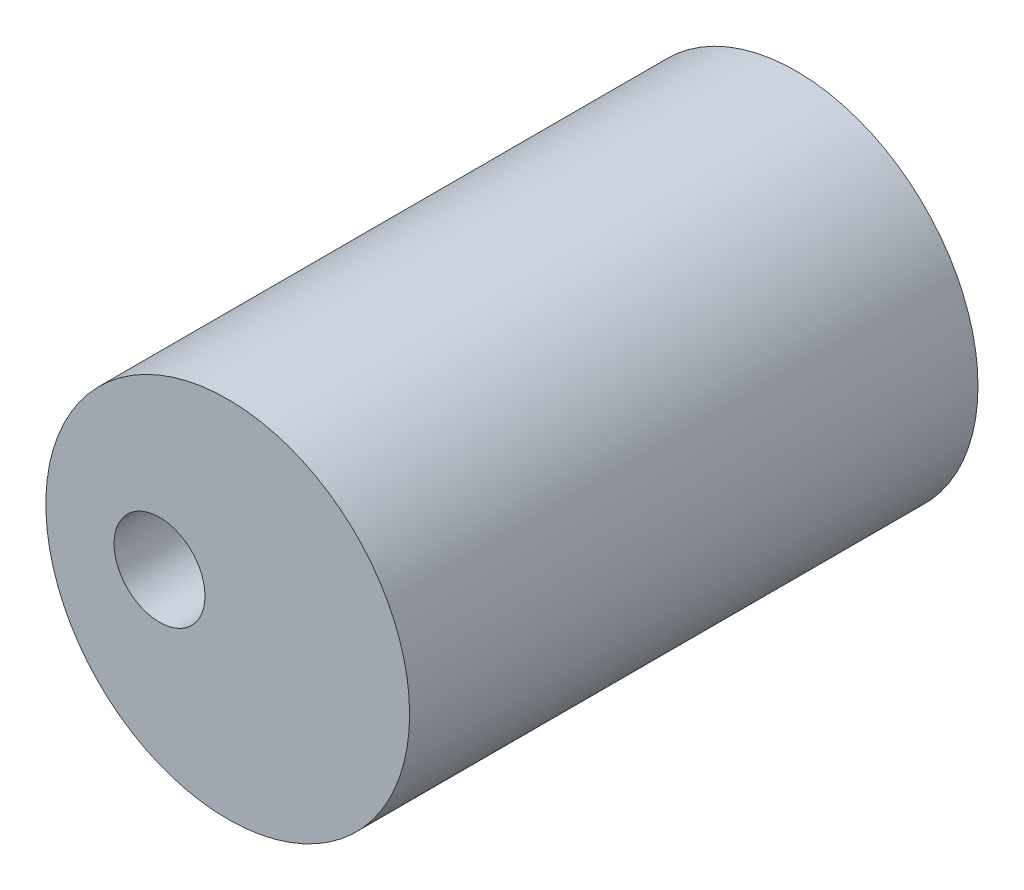
SolidWorks part; units mm, degrees
ref_plane "Front Plane" through (0, 0, 0) normal (0, 0, 1) x (1, 0, 0)
ref_plane "Top Plane" through (0, 0, 0) normal (0, 1, 0) x (1, 0, 0)
ref_plane "Right Plane" through (0, 0, 0) normal (1, 0, 0) x (0, 0, -1)
sketch "Sketch1" plane through (0, 0, 0) normal (0, 0, 1) x (1, 0, 0)
  circle A0 centre (0, 0) radius 40
  dimension "D1" = 80
extrude "Boss-Extrude1" add sketch "Sketch1" along normal blind 125
ref_plane "Plane1" through (0, 0, 18.19) normal (0, 0, 1) x (1, 0, 0)
sketch "Sketch9" plane through (0, 0, 18.19) normal (0, 0, 1) x (1, 0, 0)
  circle A0 centre (0, 0) radius 16
  dimension "D1" = 32
extrude "Cut-Extrude3" cut sketch "Sketch9" along normal blind 38.79
sketch "Sketch11" plane through (0, 0, 56.98) normal (0, 0, -1) x (-1, 0, 0)
  circle A0 centre (0, 0) radius 2.5
  dimension "D1" = 5
extrude "Cut-Extrude5" cut sketch "Sketch11" against normal blind 10
sketch "Sketch10" plane through (0, 0, 0) normal (0, 0, 1) x (1, 0, 0)
  circle A0 centre (0, 0) radius 5
  dimension "D1" = 10
extrude "Cut-Extrude4" cut sketch "Sketch10" along normal blind 38.5
sketch "Sketch12" plane through (0, 0, 0) normal (1, 0, 0) x (0, 0, -1)
  circle A0 centre (-64, 0) radius 2.5
  point P2 (0, 0)
  point P3 (-96.45, -2.5)
  point P4 (-93.962, 0)
  point P5 (-92.8736, 0)
  point P6 (-93.2559, -2.5)
  point P7 (-74.8159, 0)
  dimension "D1" = 5
  dimension "D2" = 64
extrude "Cut-Extrude7" cut sketch "Sketch12" against normal blind 44
sketch "Sketch13" plane through (0, 0, 0) normal (0, 0, -1) x (-1, 0, 0)
  line L0 (83.9172, 0) -> (-109.92, 0) construction
  circle A0 centre (25, 0) radius 2.5
  point P5 (23.006, 0)
  dimension "D1" = 5
  dimension "D2" = 25
extrude "Cut-Extrude8" cut sketch "Sketch13" against normal blind 64
sketch "Sketch14" plane through (0, 0, 0) normal (0, 0, -1) x (-1, 0, 0)
  circle A0 centre (25, 0) radius 3.25
  dimension "D1" = 6.5
extrude "Cut-Extrude9" cut sketch "Sketch14" against normal blind 20
sketch "Sketch16" plane through (0, 0, 0) normal (0, 0, -1) x (-1, 0, 0)
  circle A0 centre (11.2217, 0) radius 2.5
  point P2 (0, 0)
  point P4 (11.2217, 0)
  dimension "D1" = 5
extrude "Cut-Extrude10" cut sketch "Sketch16" against normal blind 36
ref_plane "Plane2" through (-40, 0, 0) normal (1, 0, 0) x (0, 0, -1)
sketch "Sketch18" plane through (-40, 0, 0) normal (1, 0, 0) x (0, 0, -1)
  circle A0 centre (-13.5, 0) radius 2.5
  point P2 (0, 0)
  point P4 (0, 0)
  point P5 (-13.8546, 0)
  dimension "D1" = 5
  dimension "D2" = 13.5
extrude "Cut-Extrude11" cut sketch "Sketch18" along normal blind 29
sketch "Sketch21" plane through (0, 0, 125) normal (0, 0, 1) x (1, 0, 0)
  circle A0 centre (-15, 0) radius 10
  point P2 (0, 0)
  point P3 (-17.7655, 0)
  point P4 (-14.2362, 0)
  dimension "D1" = 20
  dimension "D2" = 15
extrude "Cut-Extrude12" cut sketch "Sketch21" against normal blind 40
sketch "Sketch22" plane through (0, 0, 85) normal (0, 0, 1) x (1, 0, 0)
  circle A0 centre (-15, 0) radius 2.5
  dimension "D1" = 5
extrude "Cut-Extrude13" cut sketch "Sketch22" against normal blind 21
